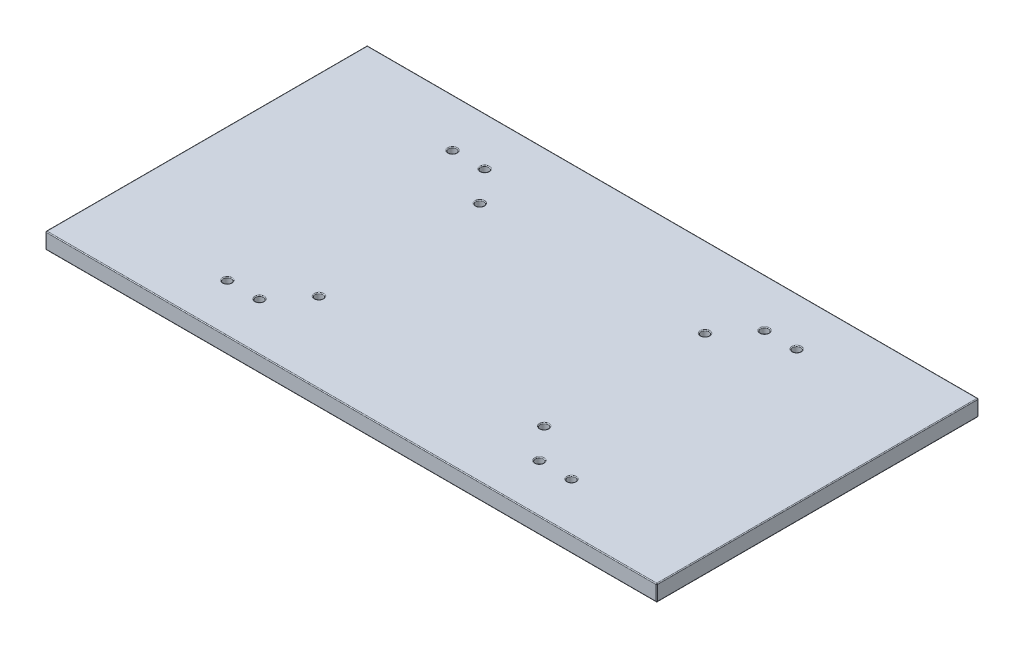
SolidWorks part; units mm, degrees
ref_plane "Front Plane" through (0, 0, 0) normal (0, 0, 1) x (1, 0, 0)
ref_plane "Top Plane" through (0, 0, 0) normal (0, 1, 0) x (1, 0, 0)
ref_plane "Right Plane" through (0, 0, 0) normal (1, 0, 0) x (0, 0, -1)
sketch "Sketch1" plane through (0, 0, 0) normal (0, 1, 0) x (1, 0, 0)
  line L0 (80, 50) -> (80, -50) construction
  line L1 (-95, 50) -> (95, 50)
  line L2 (-95, 50) -> (-95, -50)
  line L3 (-95, -50) -> (95, -50)
  line L4 (95, 50) -> (95, -50)
  line L5 (-95, 50) -> (95, -50) construction
  line L6 (-95, -50) -> (95, 50) construction
  line L7 (-35, 25) -> (35, 25) construction
  line L8 (-35, 25) -> (-35, -25) construction
  line L9 (-35, -25) -> (35, -25) construction
  line L10 (35, 25) -> (35, -25) construction
  line L11 (-35, 25) -> (35, -25) construction
  line L12 (-35, -25) -> (35, 25) construction
  line L13 (0, 50) -> (0, -50) construction
  line L14 (0, 0) -> (26.6311, 0) construction
  circle A0 centre (-35, 25) radius 1.25
  circle A2 centre (-35, -25) radius 1.25
  circle A3 centre (35, -25) radius 1.25
  circle A4 centre (35, 25) radius 1.25
  circle A5 centre (80, 0) radius 1.25
  circle A6 centre (-53.5, -35) radius 1.25
  circle A7 centre (-43.5, -35) radius 1.25
  circle A8 centre (35, -25) radius 1.25
  circle A9 centre (43.5, -35) radius 1.25
  circle A10 centre (53.5, -35) radius 1.25
  circle A11 centre (53.5, 35) radius 1.25
  circle A12 centre (43.5, 35) radius 1.25
  circle A13 centre (-43.5, 35) radius 1.25
  circle A14 centre (-53.5, 35) radius 1.25
  point P0 (0, 0)
  point P6 (0, 0)
  dimension "D5" = 2.5
  dimension "D6" = 2.5
  dimension "D7" = 2.5
  dimension "D8" = 2.5
  dimension "D10" = 2.5
  dimension "D14" = 2.5
  dimension "D1" = 190
  dimension "D2" = 100
  dimension "D3" = 70
  dimension "D4" = 50
  dimension "D9" = 15
  dimension "D11" = 10
  dimension "D12" = 43.5
  dimension "D13" = 15
extrude "Boss-Extrude1" add sketch "Sketch1" along normal blind 5 contours L2 L1 L4 L3 | A6 | A7 | A2 | A14 | A13 | A0 | A8 | A9 | A10 | A4 | A12 | A11
fillet "Fillet1" radius 0.25 36 edges at (53.5, 0, -33.75) (53.5, 5, -33.75) (43.5, 0, -33.75) (43.5, 5, -33.75) (35, 0, -23.75) (35, 5, -23.75) (53.5, 0, 33.75) (53.5, 5, 33.75) (43.5, 0, 33.75) (43.5, 5, 33.75) (35, 0, 23.75) (35, 5, 23.75) (-35, 0, -23.75) (-35, 5, -23.75) (-43.5, 0, -36.25) (-43.5, 5, -36.25) (-53.5, 0, -36.25) (-53.5, 5, -36.25) (-35, 0, 26.25) (-35, 5, 26.25) (-43.5, 0, 36.25) (-43.5, 5, 36.25) (-53.5, 0, 36.25) (-53.5, 5, 36.25) (0, 0, 50) (95, 0, 0) (0, 0, -50) (-95, 0, 0) (0, 5, 50) (95, 5, 0) (-95, 5, 0) (-95, 2.5, 50) (95, 2.5, -50) (95, 2.5, 50) (-95, 2.5, -50) (0, 5, -50)
